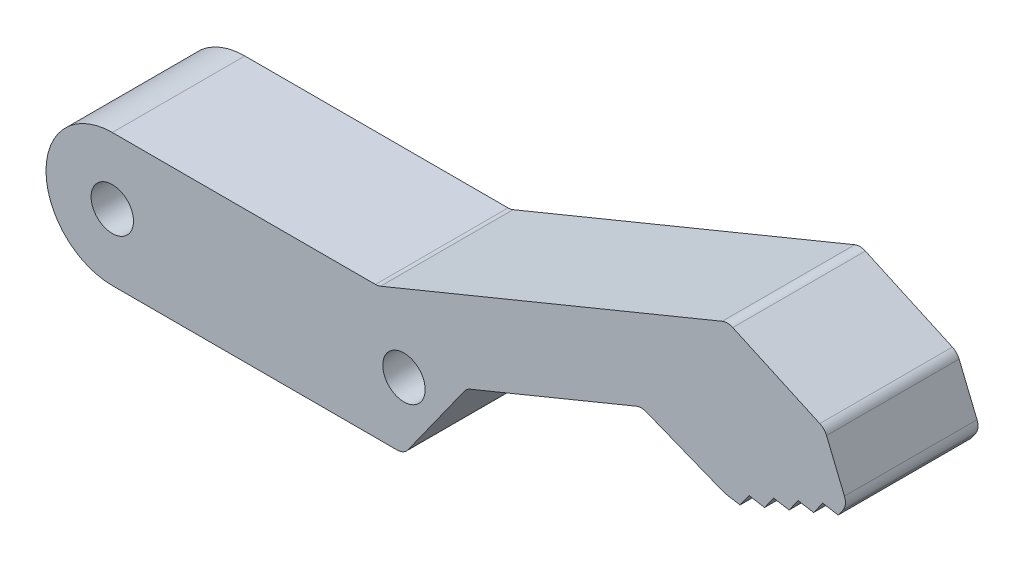
SolidWorks part; units mm, degrees
ref_plane "Front Plane" through (0, 0, 0) normal (0, 0, 1) x (1, 0, 0)
ref_plane "Top Plane" through (0, 0, 0) normal (0, 1, 0) x (1, 0, 0)
ref_plane "Right Plane" through (0, 0, 0) normal (1, 0, 0) x (0, 0, -1)
sketch "Sketch1" plane through (0, 0, 0) normal (0, 0, 1) x (1, 0, 0)
  line L0 (0, 0) -> (22, 0) construction
  line L1 (0, 5) -> (22, 5)
  line L2 (0, -5) -> (22, -5)
  line L3 (20.05, 5) -> (23.9914, -4.5863) construction
  line L4 (20.05, 5) -> (51.4959, 17.929) construction
  line L5 (23.9914, -4.5863) -> (55.4373, 8.3426) construction
  line L6 (51.4959, 17.929) -> (55.4373, 8.3426) construction
  line L7 (20.05, 5) -> (46.409, 15.8375)
  line L8 (46.409, 15.8375) -> (53.7261, 12.5046)
  line L9 (53.7261, 12.5046) -> (55.4373, 8.3426)
  line L10 (55.4373, 8.3426) -> (46.1885, 4.54) construction
  line L11 (46.1885, 4.54) -> (39.9002, 7.0361)
  line L12 (39.9002, 7.0361) -> (26.7299, 1.6211)
  line L13 (46.1885, 4.54) -> (47.351, 4.3422)
  line L14 (47.351, 4.3422) -> (48.0382, 5.3005)
  line L15 (47.351, 4.3422) -> (54.7501, 7.3843) construction
  line L16 (48.0382, 5.3005) -> (49.2008, 5.1027)
  line L17 (49.2008, 5.1027) -> (49.888, 6.0611)
  line L18 (49.888, 6.0611) -> (51.0505, 5.8633)
  line L19 (51.0505, 5.8633) -> (51.7378, 6.8216)
  line L20 (51.7378, 6.8216) -> (52.9003, 6.6238)
  line L21 (52.9003, 6.6238) -> (53.5875, 7.5821)
  line L22 (53.5875, 7.5821) -> (54.7501, 7.3843)
  line L23 (54.7501, 7.3843) -> (55.4373, 8.3426)
  line L24 (26.7299, 1.6211) -> (22, -5)
  arc A0 (0, 5) -> (0, -5) centre (0, 0) ccw
  arc A1 (22, -5) -> (22, 5) centre (22, 0) ccw
  circle A2 centre (0, 0) radius 1.5
  circle A3 centre (22, 0) radius 1.5
  point P3 (11, 0)
  dimension "D11" = 3
  dimension "D1" = 10
  dimension "D2" = 22
  dimension "D3" = 157.65
  dimension "D4" = 1.95
  dimension "D5" = 34
  dimension "D6" = 14.24
  dimension "D7" = 10
  dimension "D8" = 4.5
  dimension "D9" = 136
  dimension "D10" = 5.5
  dimension "D12" = 2
  dimension "D13" = 0.625
  dimension "D14" = 8
extrude "Boss-Extrude1" add sketch "Sketch1" along normal blind 10 contours A1 L1 A0 L2 A3 A2 | A1 L12 L11 L13 L14 L16 L17 L18 L19 L20 L21 L22 L23 L9 L8 L7 L1
fillet "Fillet1" radius 1 8 edges at (46.1885, 4.54, 5) (55.4373, 8.3426, 5) (53.7261, 12.5046, 5) (46.409, 15.8375, 5) (20.05, 5, 5) (39.9002, 7.0361, 5) (26.7299, 1.6211, 5) (22, -5, 5)
hole_wizard "M3 Clearance Hole1" positions "Sketch2" profile "Sketch4" hole size "M3" standard "ANSI Metric" end condition through all
sketch "Sketch2" plane through (0, 0, 10) normal (0, 0, 1) x (1, 0, 0)
  point P0 (0, 0)
  point P3 (22, 0)
sketch "Sketch4" plane through (0, 0, 10) normal (1, 0, 0) x (0, -1, 0)
  line L0 (0, 0) -> (0, 10)
  line L1 (0, 10) -> (1.6, 10)
  line L2 (1.6, 10) -> (1.6, 0)
  line L5 (1.6, 0) -> (0, 0)
  line L11 (0, -6.35) -> (0, 107.95) construction
  dimension "Thru Hole Dia." = 3.2
  dimension "Thru Hole Depth" = 10
